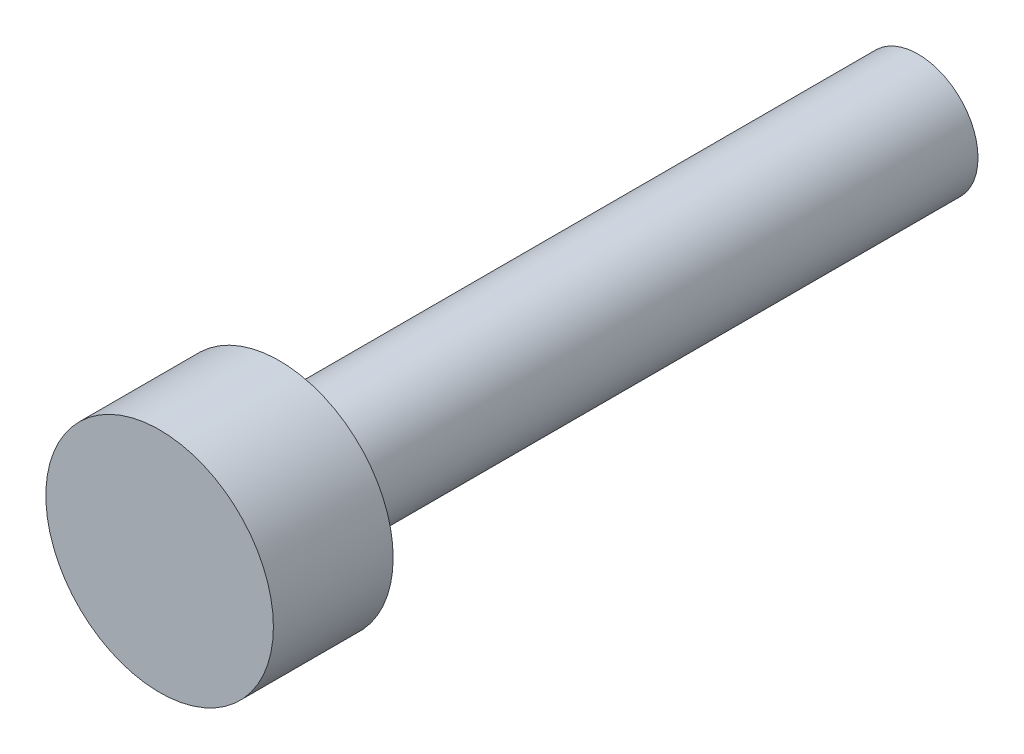
SolidWorks part; units mm, degrees
ref_plane "Front Plane" through (0, 0, 0) normal (0, 0, 1) x (1, 0, 0)
ref_plane "Top Plane" through (0, 0, 0) normal (0, 1, 0) x (1, 0, 0)
ref_plane "Right Plane" through (0, 0, 0) normal (1, 0, 0) x (0, 0, -1)
sketch "Sketch1" plane through (0, 0, 0) normal (0, 0, 1) x (1, 0, 0)
  circle A0 centre (0, 0) radius 1.5
  dimension "D1" = 3
extrude "Boss-Extrude1" add sketch "Sketch1" along normal blind 16
sketch "Sketch2" plane through (0, 0, 16) normal (0, 0, 1) x (1, 0, 0)
  circle A0 centre (0, 0) radius 2.85
  dimension "D1" = 5.7
extrude "Boss-Extrude2" add sketch "Sketch2" along normal blind 3
